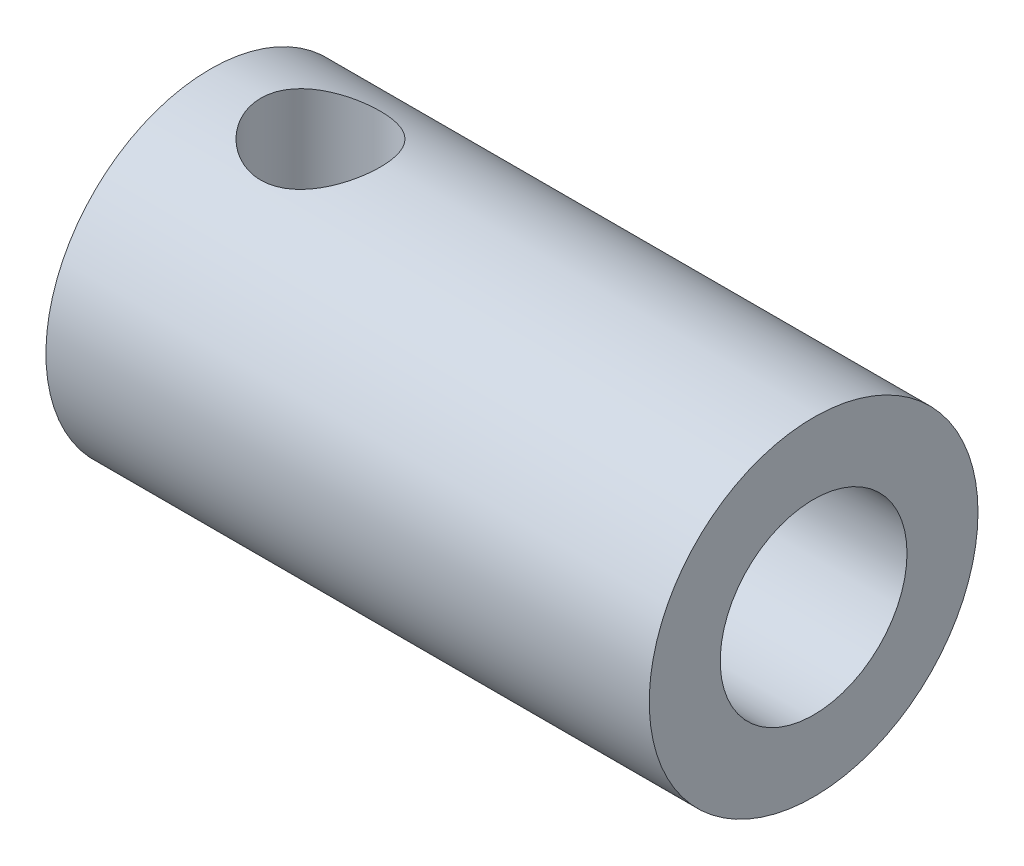
SolidWorks part; units mm, degrees
ref_plane "前视基准面" through (0, 0, 0) normal (0, 0, 1) x (1, 0, 0)
ref_plane "上视基准面" through (0, 0, 0) normal (0, 1, 0) x (1, 0, 0)
ref_plane "右视基准面" through (0, 0, 0) normal (1, 0, 0) x (0, 0, -1)
sketch "草图1" plane through (0, 0, 0) normal (0, 0, 1) x (1, 0, 0)
  line L0 (0, 0) -> (-111.8169, 0) construction
  line L1 (55, 0) -> (-55, 0) construction
  line L2 (0, 0) -> (0, 11)
  line L3 (0, -55) -> (0, 55) construction
  line L4 (0, 11) -> (-40.3731, 11)
  line L5 (0, 0) -> (-42, 0)
  arc A0 (-40.3731, 11) -> (-42, 0) centre (-4, 0) ccw
  dimension "D1" = 38
  dimension "D3" = 42
  dimension "D2" = 22
revolve "旋转1" add sketch "草图1" angle 360 about L0
sketch "草图2" plane through (0, 0, 0) normal (1, 0, 0) x (0, 0, -1)
  point P0 (0, 0)
hole_wizard "M14X1.5 螺纹孔的螺纹孔钻头1" positions "草图2" profile "草图3" hole size "M14X1.5" standard "GB"
sketch "草图3" plane through (0, 0, 0) normal (0, 1, 0) x (0, 0, -1)
  line L0 (0, 0) -> (0, 27.7554)
  line L1 (0, 27.7554) -> (6.25, 24)
  line L2 (6.25, 24) -> (6.25, 0)
  line L5 (6.25, 0) -> (0, 0)
  line L10 (0, 27.7554) -> (-6.25, 24) construction
  line L11 (0, -6.35) -> (0, 107.95) construction
  dimension "孔直径" = 12.5
  dimension "孔深度" = 24
  dimension "导头角度" = 118
sketch "草图4" plane through (0, 0, 0) normal (0, 1, 0) x (1, 0, 0)
  line L0 (-12.1, 0) -> (12.1, 0) construction
  line L1 (0, -12.1) -> (0, 12.1) construction
  circle A0 centre (-33, 0) radius 4
  dimension "D1" = 8
  dimension "D2" = 33
extrude "切除-拉伸1" cut sketch "草图4" against normal through all both and the other way through all
